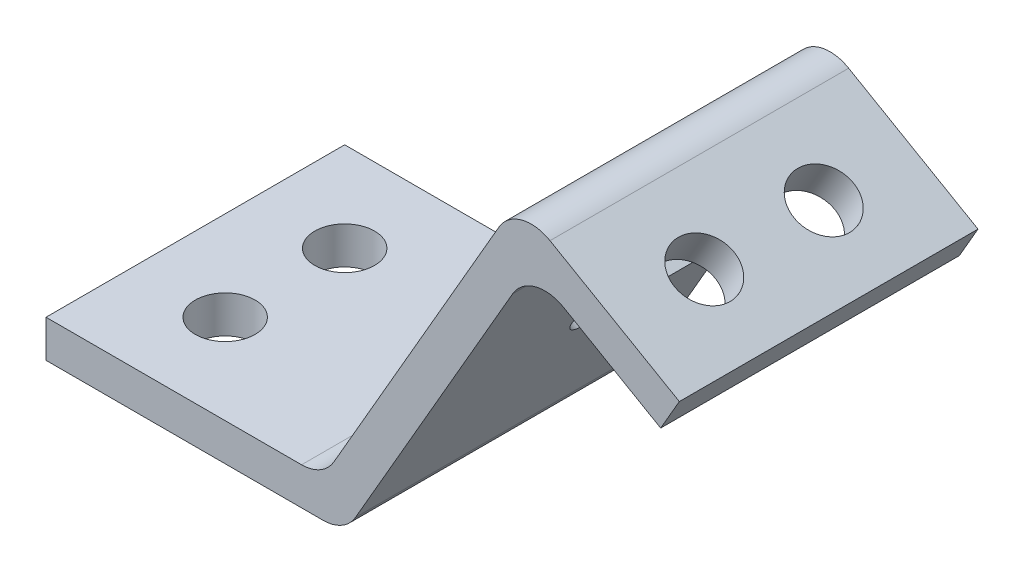
SolidWorks part; units mm, degrees
ref_plane "Front Plane" through (0, 0, 0) normal (0, 0, 1) x (1, 0, 0)
ref_plane "Top Plane" through (0, 0, 0) normal (0, 1, 0) x (1, 0, 0)
ref_plane "Right Plane" through (0, 0, 0) normal (1, 0, 0) x (0, 0, -1)
sketch "Sketch1" plane through (0, 0, 0) normal (0, 0, 1) x (1, 0, 0)
  line L0 (0, 5) -> (0, 0)
  line L1 (0, 0) -> (37.1132, 0)
  line L2 (0, 5) -> (34.2265, 5)
  line L3 (41.4434, 2.5) -> (62.5, 38.9711)
  line L4 (38.5566, 7.5) -> (60.6699, 45.8013)
  line L5 (67.5, 47.6314) -> (84.8205, 37.6314)
  line L6 (84.8205, 37.6314) -> (82.3205, 33.3013)
  line L7 (82.3205, 33.3013) -> (69.3301, 40.8013)
  arc A0 (37.1132, 0) -> (41.4434, 2.5) centre (37.1132, 5) ccw
  arc A1 (34.2265, 5) -> (38.5566, 7.5) centre (34.2265, 10) ccw
  arc A2 (67.5, 47.6314) -> (60.6699, 45.8013) centre (65, 43.3013) ccw
  arc A3 (69.3301, 40.8013) -> (62.5, 38.9711) centre (66.8301, 36.4711) ccw
  point P13 (0, 0)
  point P17 (0, 0)
  point P19 (0, 0)
  point P20 (0, 0)
  dimension "D1" = 120
  dimension "D5" = 10
  dimension "D6" = 5
  dimension "D2" = 5
  dimension "D3" = 90
  dimension "D4" = 5
  dimension "D7" = 47.1132
  dimension "D8" = 20
  dimension "D9" = 37.1132
extrude "Boss-Extrude1" add sketch "Sketch1" along normal blind 40
sketch "Sketch2" plane through (0, 5, 0) normal (0, 1, 0) x (1, 0, 0)
  line L0 (34.2265, 0) -> (0, 0) construction
  circle A0 centre (12, -12) radius 4
  circle A1 centre (12, -28) radius 4
  point P4 (16.7026, -23.8697)
  point P8 (0, 0)
  dimension "D1" = 8
  dimension "D2" = 12
  dimension "D3" = 16
  dimension "D4" = 12
extrude "Cut-Extrude1" cut sketch "Sketch2" against normal blind 40
sketch "Sketch3" plane through (25.6699, -14.8205, 0) normal (-0.866, 0.5, 0) x (0, 0, 1)
  line L0 (19, 48) -> (0, 48)
  line L1 (0, 70) -> (0, 25.7735) construction
  line L2 (19, 42) -> (0, 42)
  line L3 (0, 48) -> (0, 42)
  line L4 (40, 75) -> (0, 75) construction
  arc A0 (19, 42) -> (19, 48) centre (19, 45) ccw
  dimension "D1" = 6
  dimension "D3" = 30
  dimension "D2" = 19
extrude "Cut-Extrude2" cut sketch "Sketch3" against normal up to next
sketch "Sketch4" plane through (37.5, 64.9519, 0) normal (0.5, 0.866, 0) x (0.866, -0.5, 0)
  line L0 (54.641, -40) -> (34.641, -40) construction
  line L1 (54.641, -40) -> (54.641, 0) construction
  line L2 (54.641, 0) -> (34.641, 0) construction
  circle A0 centre (44.641, -28) radius 4
  circle A1 centre (44.641, -12) radius 4
  point P4 (45.5453, -11.906)
  point P5 (0, 0)
  point P6 (0, 0)
  dimension "D1" = 8
  dimension "D2" = 12
  dimension "D3" = 16
  dimension "D4" = 10
  dimension "D5" = 12
extrude "Cut-Extrude3" cut sketch "Sketch4" against normal up to next
